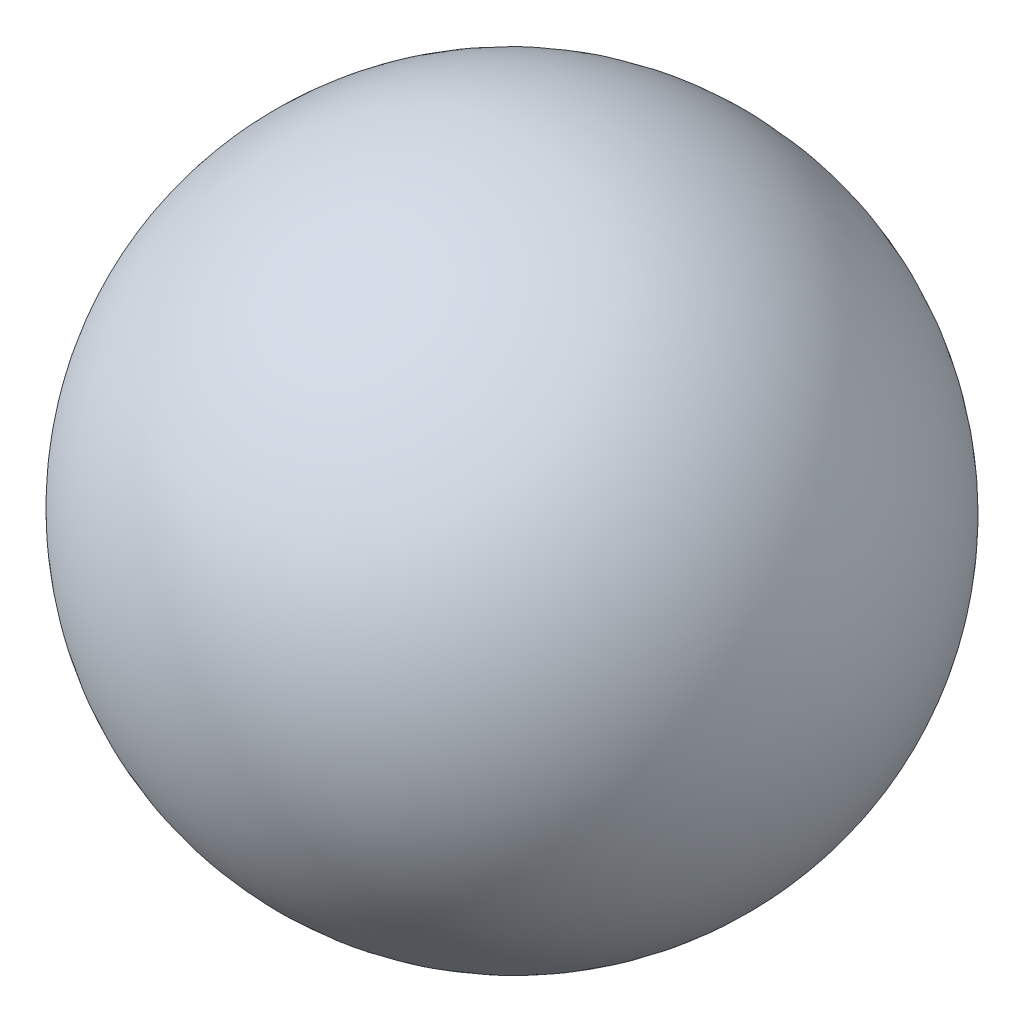
SolidWorks part; units mm, degrees
ref_plane "前基準面" through (0, 0, 0) normal (0, 0, 1) x (1, 0, 0)
ref_plane "上基準面" through (0, 0, 0) normal (0, 1, 0) x (1, 0, 0)
ref_plane "右基準面" through (0, 0, 0) normal (1, 0, 0) x (0, 0, -1)
sketch "草圖1" plane through (0, 0, 0) normal (0, 0, 1) x (1, 0, 0)
  line L0 (-14.7502, 0) -> (21.5426, -0.4718) construction
  line L1 (11.995, -0.3477) -> (-11.9999, -0.0358)
  arc A0 (-11.9999, -0.0358) -> (11.995, -0.3477) centre (0, 0) ccw
  dimension "D1" = 24
revolve "旋轉1" add sketch "草圖1" angle 360 about L0
